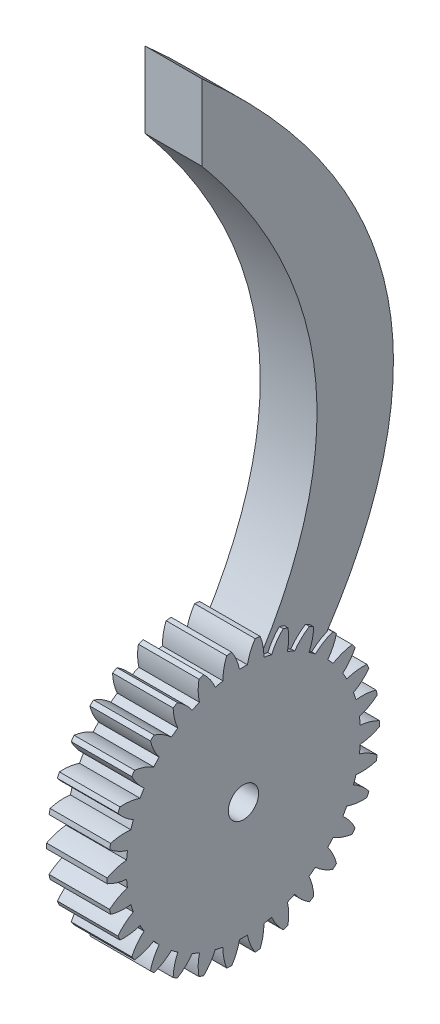
SolidWorks part; units mm, degrees
material "Nylon 101"
ref_plane "Plane1" through (0, 0, 0) normal (0, 0, 1) x (1, 0, 0)
ref_plane "Plane2" through (0, 0, 0) normal (0, 1, 0) x (1, 0, 0)
ref_plane "Plane3" through (0, 0, 0) normal (1, 0, 0) x (0, 0, -1)
other "Configuration Table"
sketch "HoldingSke" plane through (0, 0, 0) normal (0, 1, 0) x (1, 0, 0)
  line L0 (0, 0) -> (0.7698, -0.4444)
  line L1 (-15, 0) -> (100, 0) construction
  line L2 (0, 0) -> (-2.1039, 2.3779)
  line L3 (0, 0) -> (-11.863, 4.5341)
  line L4 (0, 0) -> (7.479, 4.318)
  line L5 (0, 0) -> (-46.8476, -17.4728)
  line L6 (0, 0) -> (-6.6317, -4.4744)
  line L7 (-2.1039, 2.3779) -> (8.6586, 51.2059)
  line L8 (-76.2, 54.61) -> (-75.5, 54.61)
  line L9 (-71.009, 38.7566) -> (-53.1078, 45.2721)
  line L10 (-76.2, 71.12) -> (104.1128, 71.12)
  line L11 (0, 0) -> (-8, 0)
  line L12 (-76.2, 101.6) -> (-76.158, 101.6)
  line L13 (24.9733, 27.94) -> (52.9518, 28.4284)
  line L14 (24.9733, 27.94) -> (24.9743, 27.94)
  line L15 (24.9733, 27.94) -> (100.4006, 29.5858)
  line L16 (-63.627, -1.125) -> (-12.827, -1.125)
  circle A0 centre (0, 0) radius 2
  circle A1 centre (0, 0) radius 15.4677
  circle A2 centre (0, 0) radius 37.5
  circle A3 centre (0, 0) radius 2
  dimension "MHD" = 30.9355
  dimension "Hub_dia" = 75
  dimension "Bore" = 4
  dimension "MBD" = 4
  dimension "Num_teeth" = 30
  dimension "Pitch" = 0.8889
  dimension "Overall_len" = 50
  dimension "Show_teeth" = 30
  dimension "Thickness" = 8
  dimension "OAL" = 50.0001
  dimension "T_dim" = 0.7
  dimension "Ap" = 20
  dimension "H" = 19.05
  dimension "Pitch_radius" = 180.3128
  dimension "Width" = 8
  dimension "Backlash" = 0.042
  dimension "Addendum_fac" = 1
  dimension "Dedendum_fac" = 1.25
  dimension "Clearance_fac" = 0.25
  dimension "Dedendum_add" = 0.001
  dimension "Module" = 1.125
sketch "BasProSke" plane through (0, 0, 0) normal (0, 1, 0) x (1, 0, 0)
  line L0 (-10, 0) -> (60, 0) construction
  line L1 (0, 0) -> (0, 18)
  line L2 (0, 0) -> (8, 0)
  line L3 (8, 0) -> (8, 18)
  line L4 (8, 18) -> (0, 18)
  dimension "Thickness" = 8
  dimension "Diameter" = 36
revolve "Base-Revolve" add sketch "BasProSke" angle 360 about L0
sketch "TooCutSke" plane through (0, 0, 0) normal (1, 0, 0) x (0, 0, -1)
  line L1 (0, 0) -> (0, 107) construction
  line L2 (0, 0) -> (-0.9567, 16.8479) construction
  line L3 (0, 0) -> (-3.5238, 33.5265) construction
  line L4 (-0.9567, 16.8479) -> (-1.7619, 16.7632) construction
  arc A0 (0.5235, 15.4589) -> (-0.5235, 15.4589) centre (0, 0) ccw
  arc A1 (1.5687, 17.957) -> (-1.5687, 17.957) centre (0, 0) ccw
  circle A2 centre (0, 0) radius 16.875 construction
  circle A3 centre (0, 0) radius 15.8573 construction
  arc A4 (-0.5235, 15.4589) -> (-1.5687, 17.957) centre (-7.1465, 14.1556) ccw
  arc A5 (1.5687, 17.957) -> (0.5235, 15.4589) centre (7.1465, 14.1556) ccw
  dimension "Root_dia" = 30.9355
  dimension "Overcut_dia" = 36.0508
  dimension "Pitch_dia" = 33.75
  dimension "Base_dia" = 31.7146
  dimension "Flank_rad" = 6.75
  dimension "Half_ang" = 6
  dimension "Half_CT" = 0.8097
extrude "ToothCut" cut sketch "TooCutSke" along normal through all
fillet "Breaks" [suppressed] radius 0.0225
fillet "RootFillets" [suppressed] radius 0.2822
pattern_circular "TeethCuts" count 30 every 12 about axis through (-10, 0, 0) along (1, 0, 0) of "ToothCut", "RootFillets", "Breaks"
sketch "HubNeaOneSke" plane through (0, 0, 0) normal (-1, 0, 0) x (0, 0, 1)
  circle A0 centre (0, 0) radius 15.4677
  dimension "Diameter" = 30.9355
extrude "HubNearOne" [suppressed] add sketch "HubNeaOneSke" along normal blind 42.0001
sketch "HubNeaBotSke" plane through (0, 0, 0) normal (-1, 0, 0) x (0, 0, 1)
  circle A0 centre (0, 0) radius 15.4677
  dimension "Diameter" = 30.9355
extrude "HubNearBoth" [suppressed] add sketch "HubNeaBotSke" along normal blind 21
ref_plane "FarPln" through (8, 0, 0) normal (1, 0, 0) x (0, 0, -1)
sketch "HubFarSke" plane through (8, 0, 0) normal (1, 0, 0) x (0, 0, -1)
  circle A0 centre (0, 0) radius 15.4677
  dimension "Diameter" = 30.9355
extrude "HubFar" [suppressed] add sketch "HubFarSke" along normal blind 21
sketch "BorSke" plane through (0, 0, 0) normal (1, 0, 0) x (0, 0, -1)
  circle A0 centre (0, 0) radius 2
  dimension "Diameter" = 4
extrude "Bore" cut sketch "BorSke" along normal mid plane 100.0001
sketch "KeySke" plane through (0, 0, 0) normal (1, 0, 0) x (0, 0, -1)
  line L0 (-0.8, 0) -> (-0.8, 2.7)
  line L1 (-0.8, 2.7) -> (0.8, 2.7)
  line L2 (0.8, 2.7) -> (0.8, 0)
  line L3 (0, 0) -> (0, 34) construction
  line L4 (-0.8, 0) -> (0.8, 0)
  dimension "Offset" = 2.7
  dimension "Width" = 1.6
extrude "Keyway" [suppressed] cut sketch "KeySke" along normal mid plane 100.0001
pattern_circular "Keyway2" [suppressed] count 2 every 90 about axis through (-10, 0, 0) along (1, 0, 0)
sketch "Sketch1" plane through (0, 0, 0) normal (-1, 0, 0) x (0, 0, 1)
  line L0 (-5, 5) -> (5, 5)
  line L1 (5, 85) -> (5, 75)
  spline S0 degree 2 poles (-5, 5) (-40, 45) (5, 85) knots 0 0 0 1 1 1
  spline S1 degree 2 poles (5, 5) (-25.441, 38.4023) (5, 75) knots 0 0 0 1 1 1
  point P10 (0, 0)
  dimension "D1" = 10
  dimension "D2" = 5
  dimension "D3" = 10
  dimension "D4" = 10
  dimension "D5" = 30
  dimension "D6" = 70
  dimension "D7" = 5
  dimension "D8" = 15
extrude "Boss-Extrude1" add sketch "Sketch1" against normal blind 7.5
equation "' \"Module@HoldingSke\" = 6.35"
equation "' \"Num_teeth@HoldingSke\" = 12"
equation "' \"Ap@HoldingSke\" =  20"
equation "' \"Ap@HoldingSke\" = 20"
equation "' \"Width@HoldingSke\" = 0.5 * 25.4"
equation "' \"Hub_dia@HoldingSke\"= 1 * 25.4"
equation "' \"Hub_dia@HoldingSke\" = 1 * 25.4"
equation "' \"Overall_len@HoldingSke\" = 1.0 * 25.4"
equation "' \"Bore@HoldingSke\" = 0.75 * 25.4"
equation "' \"T_dim@HoldingSke\" = 0.1 * 25.4"
equation "' \"Width@KeySke\" = 0.25 * 25.4"
equation "' \"Show_teeth@HoldingSke\" = 13"
equation "' \"Backlash@HoldingSke\" = 0.009 * 25.4"
equation "' \"Addendum_fac@HoldingSke\" = 1.0"
equation "' \"Dedendum_fac@HoldingSke\" = 1.25"
equation "' \"Dedendum_add@HoldingSke\" = 0.00005 * 25.4"
equation "' \"Clearance_fac@HoldingSke\" = 0.25"
equation "\"Pitch@HoldingSke\" = 1 / \"Module@HoldingSke\""
equation "\"Overcut_dia@TooCutSke\" = (\"Num_teeth@HoldingSke\" + 2 * \"Addendum_fac@HoldingSke\") / \"Pitch@HoldingSke\" + 0.002 * 25.4"
equation "\"Pitch_dia@TooCutSke\" = \"Num_teeth@HoldingSke\" / \"Pitch@HoldingSke\""
equation "\"Base_dia@TooCutSke\" = \"Num_teeth@HoldingSke\" / \"Pitch@HoldingSke\" * cos((\"Ap@HoldingSke\"  * 3.14159265 / 180))"
equation "\"Root_dia@TooCutSke\" = (\"Num_teeth@HoldingSke\" + 2) / \"Pitch@HoldingSke\" - 2 * (\"Addendum_fac@HoldingSke\" + \"Dedendum_fac@HoldingSke\") / \"Pitch@HoldingSke\" - \"Dedendum_add@HoldingSke\" * 2"
equation "\"Half_ang@TooCutSke\" = 180 / \"Num_teeth@HoldingSke\""
equation "\"Half_CT@TooCutSke\" = \"Num_teeth@HoldingSke\" / \"Pitch@HoldingSke\" * sin((3.14159265 / 2 / \"Num_teeth@HoldingSke\")) / 2 - 7 * \"Backlash@HoldingSke\" / 4"
equation "\"Flank_rad@TooCutSke\" = \"Num_teeth@HoldingSke\" / \"Pitch@HoldingSke\" / 5"
equation "\"Radius@RootFillets\" = \"Clearance_fac@HoldingSke\" / \"Pitch@HoldingSke\" + \"Dedendum_add@HoldingSke\""
equation "\"Break_rad@Breaks\" = 0.02 / \"Pitch@HoldingSke\""
equation "\"Thickness@HoldingSke\" = \"Width@HoldingSke\""
equation "\"OAL@HoldingSke\" = \"Thickness@HoldingSke\""
equation "\"MHD@HoldingSke\" = (\"Num_teeth@HoldingSke\" + 2) / \"Pitch@HoldingSke\" - 2 * (\"Addendum_fac@HoldingSke\" + \"Dedendum_fac@HoldingSke\")  / \"Pitch@HoldingSke\" - \"Dedendum_add@HoldingSke\" * 2"
equation "\"MBD@HoldingSke\" = (\"Num_teeth@HoldingSke\" + 2) / \"Pitch@HoldingSke\" - 2 * (\"Addendum_fac@HoldingSke\" + \"Dedendum_fac@HoldingSke\")  / \"Pitch@HoldingSke\" - \"Dedendum_add@HoldingSke\" * 2 - 0.002 * 25.4"
equation "\"MHD@HoldingSke\" = ((sgn( \"MHD@HoldingSke\" - \"Hub_dia@HoldingSke\" )-1)*( \"MHD@HoldingSke\" - \"Hub_dia@HoldingSke\" ))/-2+ \"Hub_dia@HoldingSke\""
equation "\"MBD@HoldingSke\" = ((sgn( \"MBD@HoldingSke\" - \"Bore@HoldingSke\" )-1)*( \"MBD@HoldingSke\" - \"Bore@HoldingSke\" ))/-2+ \"Bore@HoldingSke\""
equation "\"OAL@HoldingSke\" = ((sgn( \"OAL@HoldingSke\" - \"Overall_len@HoldingSke\" )+1)*( \"OAL@HoldingSke\" - \"Overall_len@HoldingSke\" ))/2 + \"Overall_len@HoldingSke\" + 0.000002 * 25.4"
equation "\"Num_teeth@TeethCuts\" = int( \"Show_teeth@HoldingSke\" ) + 1"
equation "\"Num_teeth@TeethCuts\" = ((sgn( \"Num_teeth@TeethCuts\" - \"Num_teeth@HoldingSke\" )-1)*( \"Num_teeth@TeethCuts\" - \"Num_teeth@HoldingSke\" ))/-2+ \"Num_teeth@HoldingSke\""
equation "\"Num_teeth@TeethCuts\" = ((sgn( \"Num_teeth@TeethCuts\" - 2.0)+1)*( \"Num_teeth@TeethCuts\" - 2.0))/2 +2.0"
equation "\"Angle@TeethCuts\" = 360.0 / \"Num_teeth@HoldingSke\""
equation "\"Diameter@BasProSke\" = (\"Num_teeth@HoldingSke\" + 2 * \"Addendum_fac@HoldingSke\") / \"Pitch@HoldingSke\""
equation "\"Thickness@BasProSke\"  = \"Thickness@HoldingSke\""
equation "' \"Fillet_rad@BasProSke\" =  \"Thickness@HoldingSke\" * 0.05"
equation "' \"Fillet_rad@BasProSke\" = \"Thickness@HoldingSke\" * 0.05"
equation "\"MHD@HoldingSke\" = ((sgn( \"MHD@HoldingSke\" - \"Root_dia@TooCutSke\" )-1)*( \"MHD@HoldingSke\" - \"Root_dia@TooCutSke\" ))/-2+ \"Root_dia@TooCutSke\""
equation "\"Diameter@HubNeaOneSke\" = \"MHD@HoldingSke\""
equation "\"Length@HubNearOne\" = \"OAL@HoldingSke\" - \"Thickness@BasProSke\""
equation "\"Diameter@HubNeaBotSke\" = \"MHD@HoldingSke\""
equation "\"Length@HubNearBoth\" = ( \"OAL@HoldingSke\" - \"Thickness@BasProSke\" ) / 2.0"
equation "\"Thickness@FarPln\" = \"Thickness@BasProSke\""
equation "\"Diameter@HubFarSke\" = \"MHD@HoldingSke\""
equation "\"Length@HubFar\" = ( \"OAL@HoldingSke\" - \"Thickness@BasProSke\" ) / 2.0"
equation "\"Diameter@BorSke\" = \"MBD@HoldingSke\""
equation "\"D1@Bore\" = \"OAL@HoldingSke\" * 2.0"
equation "\"D1@Keyway\" = \"OAL@HoldingSke\" * 2.0"
equation "\"Offset@KeySke\" = \"T_dim@HoldingSke\" + \"MBD@HoldingSke\" / 2.0"
